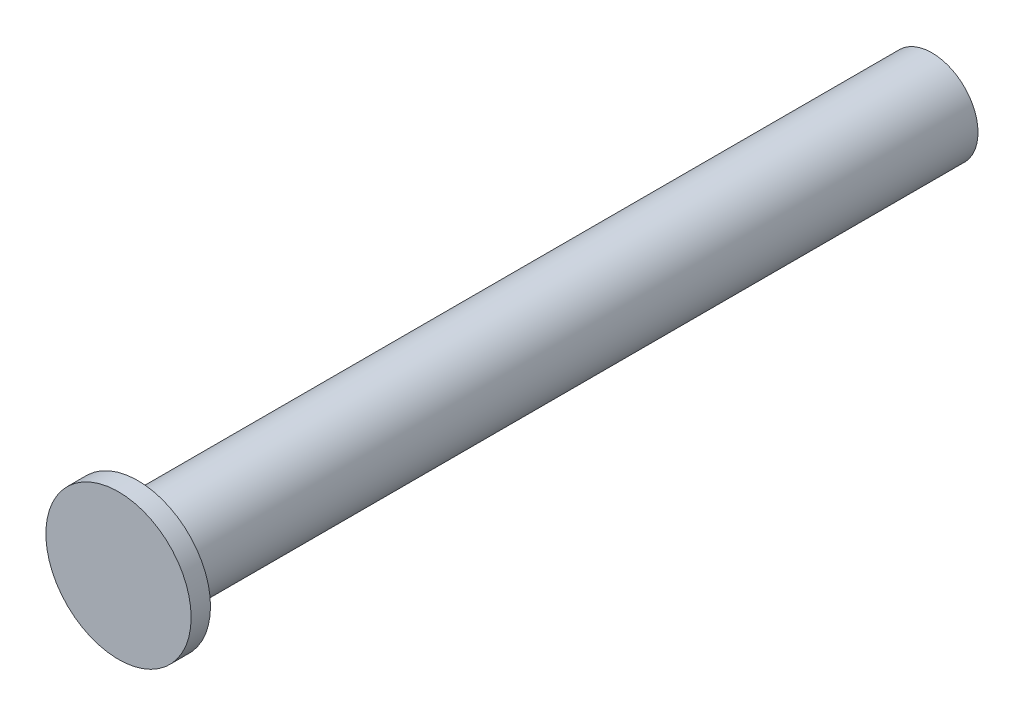
SolidWorks part; units mm, degrees
ref_plane "前视基准面" through (0, 0, 0) normal (0, 0, 1) x (1, 0, 0)
ref_plane "上视基准面" through (0, 0, 0) normal (0, 1, 0) x (1, 0, 0)
ref_plane "右视基准面" through (0, 0, 0) normal (1, 0, 0) x (0, 0, -1)
sketch "草图1" plane through (0, 0, 0) normal (0, 0, 1) x (1, 0, 0)
  circle A0 centre (0, 0) radius 4.75
  dimension "D1" = 9.5
extrude "凸台-拉伸1" add sketch "草图1" along normal blind 82
sketch "草图2" plane through (0, 0, 82) normal (0, 0, 1) x (1, 0, 0)
  circle A0 centre (0, 0) radius 7.5
  dimension "D1" = 15
extrude "凸台-拉伸2" add sketch "草图2" along normal blind 2
